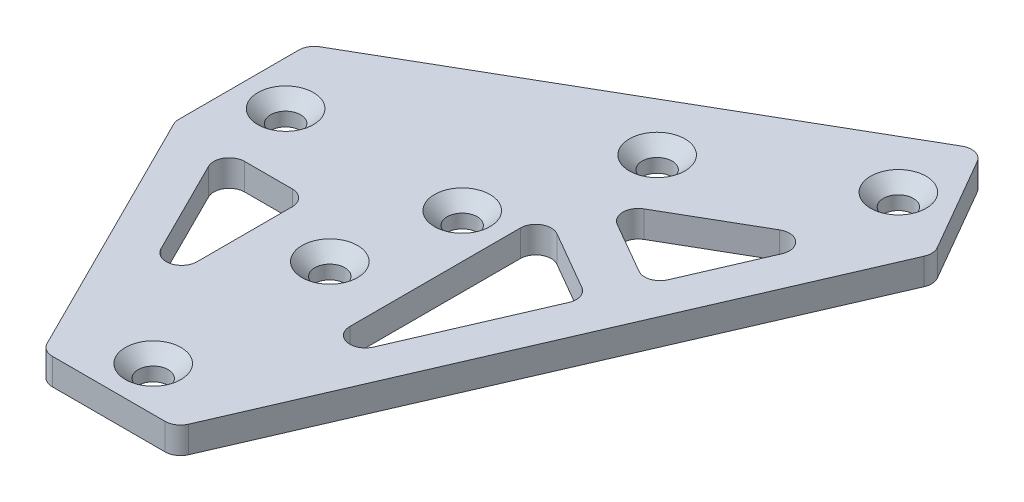
SolidWorks part; units mm, degrees
ref_plane "正面" through (0, 0, 0) normal (0, 0, 1) x (1, 0, 0)
ref_plane "平面" through (0, 0, 0) normal (0, 1, 0) x (1, 0, 0)
ref_plane "右側面" through (0, 0, 0) normal (1, 0, 0) x (0, 0, -1)
sketch "ｽｹｯﾁ2" plane through (0, 0.3953, 0) normal (0, 1, 0) x (1, 0, 0)
  line L0 (275.032, 154.7676) -> (267.532, 167.7579) construction
  line L1 (267.532, 167.7579) -> (163.6089, 107.7579) construction
  line L2 (163.6089, 107.7579) -> (171.1089, 94.7676) construction
  line L3 (171.1089, 94.7676) -> (275.032, 154.7676) construction
  line L4 (171.1089, 79.7676) -> (156.1089, 79.7676) construction
  line L5 (156.1089, 79.7676) -> (156.1089, -61.2324) construction
  line L6 (156.1089, -61.2324) -> (171.1089, -61.2324) construction
  line L7 (171.1089, -61.2324) -> (171.1089, 79.7676) construction
  line L8 (171.1089, 79.7676) -> (171.1089, 94.7676) construction
  line L9 (171.1089, 94.7676) -> (-48.8911, 94.7676) construction
  line L11 (-48.8911, 79.7676) -> (171.1089, 79.7676) construction
  line L12 (275.032, 154.7676) -> (267.532, 167.7579) construction
  line L13 (267.532, 167.7579) -> (163.6089, 107.7579) construction
  line L14 (163.6089, 107.7579) -> (171.1089, 94.7676) construction
  line L15 (171.1089, 94.7676) -> (275.032, 154.7676) construction
  line L16 (171.1089, 79.7676) -> (156.1089, 79.7676) construction
  line L17 (156.1089, 79.7676) -> (156.1089, -61.2324) construction
  line L18 (156.1089, -61.2324) -> (171.1089, -61.2324) construction
  line L19 (171.1089, -61.2324) -> (171.1089, 79.7676) construction
  line L20 (171.1089, 79.7676) -> (171.1089, 94.7676) construction
  line L21 (171.1089, 94.7676) -> (-48.8911, 94.7676) construction
  line L23 (-48.8911, 79.7676) -> (171.1089, 79.7676) construction
  line L24 (0, 15) -> (103.923, 75) construction
  line L25 (0, 0) -> (-220, 0) construction
  line L26 (0, 0) -> (0, 15) construction
  line L27 (0, 15) -> (-220, 15) construction
  line L28 (-220, 0) -> (-220, 15) construction
  line L29 (0, 0) -> (-15, 0) construction
  line L30 (0, 0) -> (0, -141) construction
  line L31 (0, -141) -> (-15, -141) construction
  line L32 (-15, 0) -> (-15, -141) construction
  line L33 (103.923, 75) -> (96.423, 87.9904) construction
  line L34 (96.423, 87.9904) -> (-7.5, 27.9904) construction
  line L35 (-7.5, 27.9904) -> (0, 15) construction
  dimension "D1" = 15
  dimension "D2" = 220
  dimension "D3" = 141
  dimension "D4" = 15
  dimension "D5" = 120
  dimension "D6" = 15
  dimension "D7" = 120
sketch "ｽｹｯﾁ4" plane through (0, 0, 0) normal (0, 1, 0) x (1, 0, 0)
  line L0 (103.923, 75) -> (96.423, 87.9904) construction
  line L1 (0, 15) -> (103.923, 75) construction
  line L2 (96.423, 87.9904) -> (-7.5, 27.9904) construction
  line L3 (-7.5, 27.9904) -> (0, 15) construction
  line L4 (0, -141) -> (-15, -141) construction
  line L5 (0, 0) -> (0, -141) construction
  line L6 (-15, 0) -> (-15, -141) construction
  line L7 (0, 0) -> (0, 15) construction
  line L8 (-220, 0) -> (-220, 15) construction
  line L9 (0, 0) -> (-220, 0) construction
  line L10 (0, 15) -> (-220, 15) construction
  line L11 (103.923, 75) -> (96.423, 87.9904) construction
  line L12 (0, 15) -> (103.923, 75) construction
  line L13 (96.423, 87.9904) -> (-7.5, 27.9904) construction
  line L14 (-7.5, 27.9904) -> (0, 15) construction
  line L15 (0, -141) -> (-15, -141) construction
  line L16 (0, 0) -> (0, -141) construction
  line L17 (-15, 0) -> (-15, -141) construction
  line L18 (0, 0) -> (0, 15) construction
  line L19 (-220, 0) -> (-220, 15) construction
  line L20 (0, 0) -> (-220, 0) construction
  line L21 (0, 15) -> (-220, 15) construction
  line L22 (-3.75, 21.4952) -> (17.9006, 33.9952) construction
  line L23 (0, 7.5) -> (-25, 7.5) construction
  line L24 (-7.5, 0) -> (-7.5, -25) construction
  line L25 (-30, 0) -> (-30, 15)
  line L26 (-30, 15) -> (18.4808, 42.9904)
  line L27 (18.4808, 42.9904) -> (25.9808, 30)
  line L28 (25.9808, 30) -> (0, -30)
  line L29 (0, -30) -> (-15, -30)
  line L30 (-15, -30) -> (-30, 0)
  circle A0 centre (0.5801, 23.9952) radius 1.6
  circle A1 centre (-5, 7.5) radius 1.6
  circle A2 centre (-7.5, -5) radius 1.6
  circle A3 centre (-7.5, -25) radius 1.6
  circle A4 centre (-25, 7.5) radius 1.6
  circle A5 centre (17.9006, 33.9952) radius 1.6
  dimension "D4" = 3.2
  dimension "D5" = 3.2
  dimension "D6" = 3.2
  dimension "D7" = 3.2
  dimension "D8" = 3.2
  dimension "D9" = 3.2
  dimension "D1" = 25
  dimension "D2" = 25
  dimension "D3" = 25
  dimension "D10" = 20
  dimension "D11" = 20
  dimension "D12" = 20
  dimension "D13" = 5
  dimension "D14" = 5
  dimension "D15" = 5
extrude "ﾎﾞｽ - 押し出し1" add sketch "ｽｹｯﾁ4" along normal mid plane 3
sketch "ｽｹｯﾁ5" plane through (0, 1.5, 0) normal (0, 1, 0) x (1, 0, 0)
  line L0 (-7.5, 27.9904) -> (0, 15) construction
  line L1 (0, 15) -> (103.923, 75) construction
  line L2 (0, 0) -> (0, 15) construction
  line L3 (0, 15) -> (-220, 15) construction
  line L4 (0, 0) -> (-220, 0) construction
  line L5 (-15, 0) -> (-15, -141) construction
  line L6 (-30, 0) -> (-15, -30)
  line L7 (-15, -30) -> (0, -30)
  line L8 (0, -30) -> (25.9808, 30)
  line L9 (25.9808, 30) -> (18.4808, 42.9904)
  line L10 (18.4808, 42.9904) -> (-30, 15)
  line L11 (-30, 15) -> (-30, 0)
  line L12 (-30, 0) -> (-15, -30)
  line L13 (-15, -30) -> (0, -30)
  line L14 (0, -30) -> (25.9808, 30)
  line L15 (25.9808, 30) -> (18.4808, 42.9904)
  line L16 (18.4808, 42.9904) -> (-30, 15)
  line L17 (-30, 15) -> (-30, 0)
  line L18 (0, 0) -> (0, -141) construction
  line L19 (-7.5, 27.9904) -> (0, 15)
  line L20 (0, 15) -> (103.923, 75)
  line L21 (0, 0) -> (0, 15)
  line L22 (0, 15) -> (-220, 15)
  line L23 (0, 0) -> (-220, 0)
  line L24 (-15, 0) -> (-15, -141)
  line L25 (0, 0) -> (0, -141)
  line L26 (-2.9552, -25.5) -> (20.9517, 29.7106)
  line L27 (20.9517, 29.7106) -> (16.8336, 36.8433)
  line L28 (16.8336, 36.8433) -> (-25.5, 12.4019)
  line L29 (-25.5, 12.4019) -> (-25.5, 1.0623)
  line L30 (-25.5, 1.0623) -> (-12.2188, -25.5)
  line L31 (-12.2188, -25.5) -> (-2.9552, -25.5)
  line L32 (0, 15) -> (11.6654, 8.265) construction
  line L33 (0, 15) -> (-10.5, 21.0622) construction
  line L34 (-13, 19.6188) -> (10.6654, 5.9555)
  line L37 (-21, 15) -> (-5.25, 24.0933) construction
  line L38 (12.6654, 10.5744) -> (-8, 22.5056)
  line L40 (0, 15) -> (3.4641, 13)
  line L41 (0, 15) -> (-3.4641, 17)
  line L42 (-4.6188, 15) -> (-2.3094, 19)
  line L43 (0, 7) -> (6.9282, 19)
  line L44 (1.25, 17.1651) -> (-9.25, 23.2272) construction
  line L47 (-1.25, 12.8349) -> (10.4154, 6.0999) construction
  circle A1 centre (0.5801, 23.9952) radius 1.6
  circle A2 centre (0.5801, 23.9952) radius 1.6
  circle A3 centre (-5, 7.5) radius 1.6
  circle A4 centre (-5, 7.5) radius 1.6
  circle A5 centre (-7.5, -5) radius 1.6
  circle A6 centre (-7.5, -5) radius 1.6
  circle A7 centre (-7.5, -25) radius 1.6
  circle A8 centre (-7.5, -25) radius 1.6
  circle A9 centre (-25, 7.5) radius 1.6
  circle A10 centre (-25, 7.5) radius 1.6
  circle A11 centre (17.9006, 33.9952) radius 1.6
  circle A12 centre (17.9006, 33.9952) radius 1.6
  point P58 (-3.4641, 17)
  point P61 (3.4641, 13)
  dimension "D9" = 2.5
  dimension "D12" = 60
  dimension "D13" = 4
  dimension "D14" = 4
  dimension "D1" = 0
  dimension "D2" = 0
  dimension "D3" = 0
  dimension "D4" = 0
  dimension "D5" = 0
  dimension "D6" = 0
  dimension "D7" = 0
  dimension "D8" = 4.5
extrude "ｶｯﾄ - 押し出し2" cut sketch "ｽｹｯﾁ5" against normal blind 3 contours L43 L38 L26 L20 | L38 L43 L20 | L21 L43 L34 | L43 L21 L25 L26 L34 | L23 L30 L24
fillet "ﾌｨﾚｯﾄ2" radius 1.75 15 edges at (-15, 0, 19.9377) (0, 0, 18.6752) (10.6654, 0, -5.9555) (12.6654, 0, -10.5744) (2.5, 0, -16.4434) (19.4424, 0, -26.2251) (-24.9688, 0, 0) (-15, 0, 30) (0, 0, 30) (25.9808, 0, -30) (18.4808, 0, -42.9904) (-30, 0, -15) (-30, 0, 0) (0, 0, -12.1132) (-15, 0, 0)
sketch "ｽｹｯﾁ6" plane through (0, 1.5, 0) normal (0, 1, 0) x (1, 0, 0)
  line L3 (-23.7025, -2.5326) -> (-18.3152, -13.3072)
  line L4 (-16.75, 0) -> (-22.1373, 0)
  line L5 (-15, -12.5246) -> (-15, -1.75)
  line L6 (-23.7025, -2.5326) -> (-18.3152, -13.3072)
  line L7 (-16.75, 0) -> (-22.1373, 0)
  line L8 (-15, -12.5246) -> (-15, -1.75)
  line L9 (3.3559, -10.9251) -> (10.0457, 4.5244)
  line L10 (0, 9.0822) -> (0, -10.2297)
  line L11 (9.3148, 6.7353) -> (2.625, 10.5977)
  line L12 (3.3559, -10.9251) -> (10.0457, 4.5244)
  line L13 (0, 9.0822) -> (0, -10.2297)
  line L14 (9.3148, 6.7353) -> (2.625, 10.5977)
  line L15 (5.125, 14.9278) -> (10.9648, 11.5562)
  line L16 (14.8581, 23.5783) -> (5.125, 17.9589)
  line L17 (13.4457, 12.3764) -> (17.339, 21.3674)
  line L18 (5.125, 14.9278) -> (10.9648, 11.5562)
  line L19 (14.8581, 23.5783) -> (5.125, 17.9589)
  line L20 (13.4457, 12.3764) -> (17.339, 21.3674)
  circle A1 centre (0.5801, 23.9952) radius 1.6
  circle A2 centre (0.5801, 23.9952) radius 1.6
  arc A3 (-22.1373, 0) -> (-23.7025, -2.5326) centre (-22.1373, -1.75) ccw
  arc A4 (-15, -1.75) -> (-16.75, 0) centre (-16.75, -1.75) ccw
  arc A5 (-18.3152, -13.3072) -> (-15, -12.5246) centre (-16.75, -12.5246) ccw
  arc A6 (-22.1373, 0) -> (-23.7025, -2.5326) centre (-22.1373, -1.75) ccw
  arc A7 (-15, -1.75) -> (-16.75, 0) centre (-16.75, -1.75) ccw
  arc A8 (-18.3152, -13.3072) -> (-15, -12.5246) centre (-16.75, -12.5246) ccw
  arc A9 (0, -10.2297) -> (3.3559, -10.9251) centre (1.75, -10.2297) ccw
  arc A10 (2.625, 10.5977) -> (0, 9.0822) centre (1.75, 9.0822) ccw
  arc A11 (10.0457, 4.5244) -> (9.3148, 6.7353) centre (8.4398, 5.2198) ccw
  arc A12 (0, -10.2297) -> (3.3559, -10.9251) centre (1.75, -10.2297) ccw
  arc A13 (2.625, 10.5977) -> (0, 9.0822) centre (1.75, 9.0822) ccw
  arc A14 (10.0457, 4.5244) -> (9.3148, 6.7353) centre (8.4398, 5.2198) ccw
  arc A15 (5.125, 17.9589) -> (5.125, 14.9278) centre (6, 16.4434) ccw
  arc A16 (17.339, 21.3674) -> (14.8581, 23.5783) centre (15.7331, 22.0628) ccw
  arc A17 (10.9648, 11.5562) -> (13.4457, 12.3764) centre (11.8398, 13.0717) ccw
  arc A18 (5.125, 17.9589) -> (5.125, 14.9278) centre (6, 16.4434) ccw
  arc A19 (17.339, 21.3674) -> (14.8581, 23.5783) centre (15.7331, 22.0628) ccw
  arc A20 (10.9648, 11.5562) -> (13.4457, 12.3764) centre (11.8398, 13.0717) ccw
  circle A21 centre (-5, 7.5) radius 1.6
  circle A22 centre (-5, 7.5) radius 1.6
  circle A23 centre (-7.5, -5) radius 1.6
  circle A24 centre (-7.5, -5) radius 1.6
  circle A25 centre (-7.5, -25) radius 1.6
  circle A26 centre (-7.5, -25) radius 1.6
  circle A27 centre (-25, 7.5) radius 1.6
  circle A28 centre (-25, 7.5) radius 1.6
  circle A29 centre (17.9006, 33.9952) radius 1.6
  circle A30 centre (17.9006, 33.9952) radius 1.6
  dimension "D1" = 0
  dimension "D2" = 0
  dimension "D3" = 0
  dimension "D4" = 0
  dimension "D5" = 0
  dimension "D6" = 0
  dimension "D7" = 0
  dimension "D8" = 0
  dimension "D9" = 0
hole_wizard "M3 丸皿ねじ用皿穴1" positions "3Dｽｹｯﾁ2" profile "ｽｹｯﾁ8" countersink size "M3" standard "ISO"
sketch3d "3Dｽｹｯﾁ2"
  point P0 (-25, 1.5, -7.5)
  point P3 (-5, 1.5, -7.5)
  point P6 (-7.5, 1.5, 5)
  point P9 (-7.5, 1.5, 25)
  point P12 (0.5801, 1.5, -23.9952)
  point P15 (17.9006, 1.5, -33.9952)
sketch "ｽｹｯﾁ8" plane through (-25, 1.5, -7.5) normal (1, 0, 0) x (0, 0, 1)
  line L0 (0, 0) -> (0, 7)
  line L1 (0, 7) -> (1.7, 5.9785)
  line L2 (1.7, 5.9785) -> (1.7, 1.45)
  line L3 (1.7, 1.45) -> (3.15, 0)
  line L5 (3.15, 0) -> (0, 0)
  line L6 (-1.7, 1.45) -> (-3.15, 0) construction
  line L10 (0, 7) -> (-1.7, 5.9785) construction
  line L11 (0, -6.35) -> (0, 107.95) construction
  dimension "穴の直径" = 3.4
  dimension "穴の深さ" = 7
  dimension "表面の皿穴の直径" = 6.3
  dimension "表面の皿穴の角度" = 90
  dimension "ﾄﾞﾘﾙ角度" = 118
